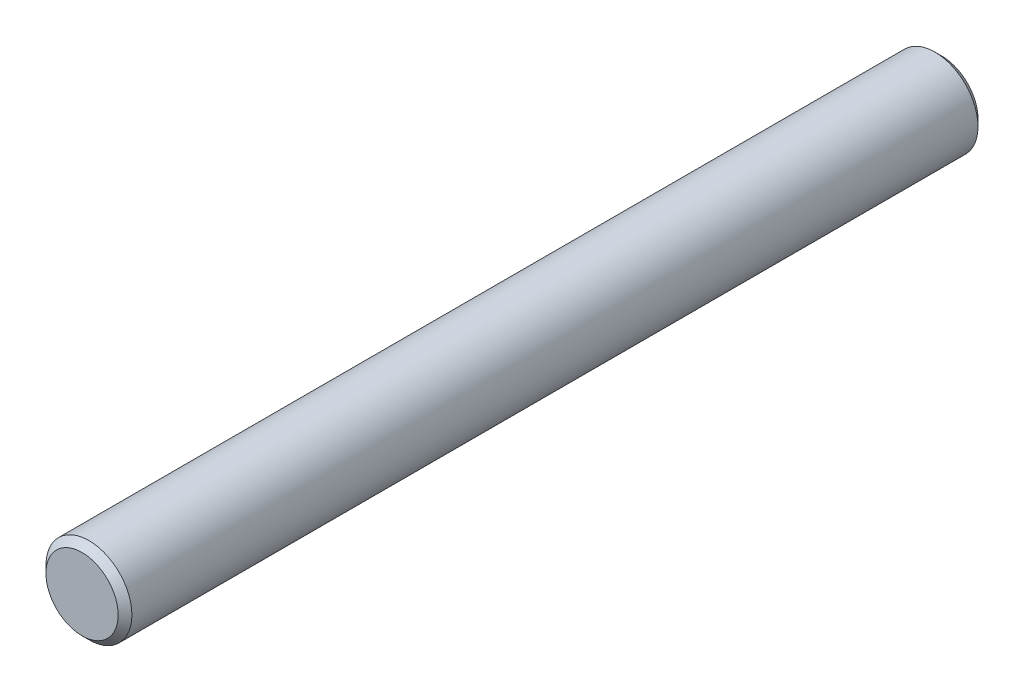
SolidWorks part; units mm, degrees
ref_plane "Front Plane" through (0, 0, 0) normal (0, 0, 1) x (1, 0, 0)
ref_plane "Top Plane" through (0, 0, 0) normal (0, 1, 0) x (1, 0, 0)
ref_plane "Right Plane" through (0, 0, 0) normal (1, 0, 0) x (0, 0, -1)
sketch "Sketch1" plane through (0, 0, 0) normal (0, 0, 1) x (1, 0, 0)
  circle A0 centre (0, 0) radius 1.5875
  dimension "D1" = 3.175
extrude "Boss-Extrude1" add sketch "Sketch1" along normal mid plane 31.75
chamfer "Chamfer1" distance 0.254 angle 45 2 edges at (1.5875, 0, -15.875) (1.5875, 0, 15.875)
